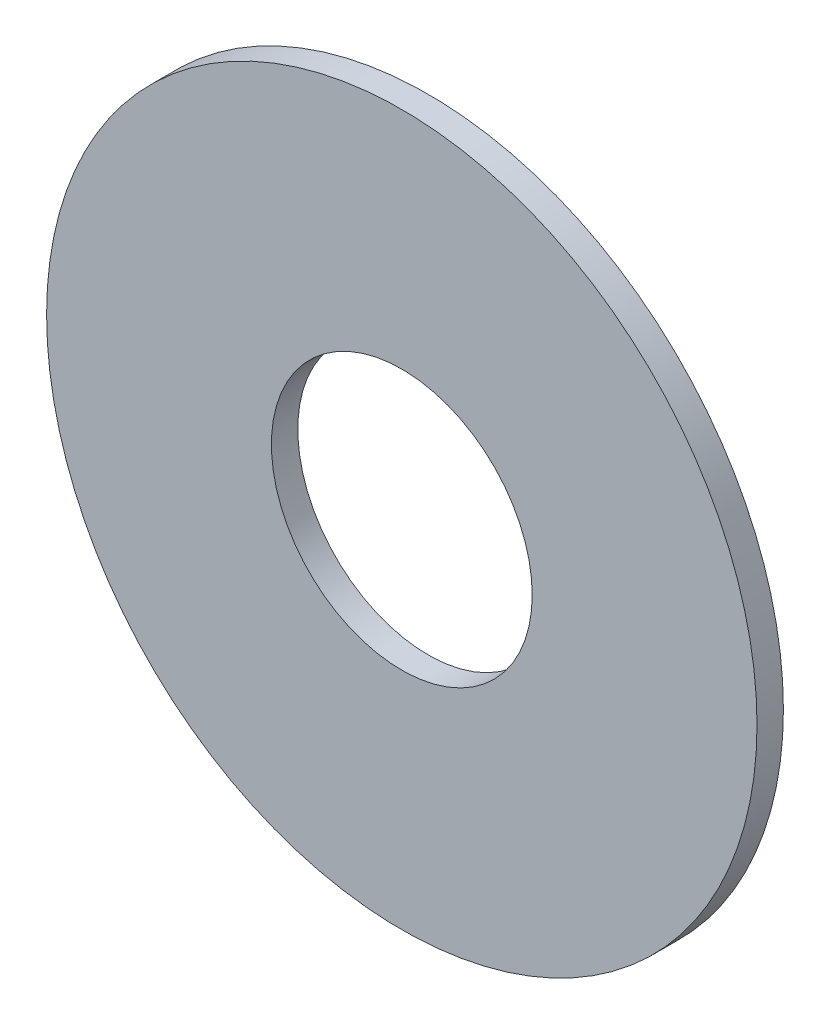
SolidWorks part; units mm, degrees
ref_plane "Front Plane" through (0, 0, 0) normal (0, 0, 1) x (1, 0, 0)
ref_plane "Top Plane" through (0, 0, 0) normal (0, 1, 0) x (1, 0, 0)
ref_plane "Right Plane" through (0, 0, 0) normal (1, 0, 0) x (0, 0, -1)
sketch "Sketch1" plane through (0, 0, 0) normal (0, 0, 1) x (1, 0, 0)
  circle A0 centre (0, 0) radius 3.2639
  circle A1 centre (0, 0) radius 8.89
  dimension "D1" = 6.5278
  dimension "D2" = 17.78
extrude "Boss-Extrude1" add sketch "Sketch1" along normal blind 0.6604
